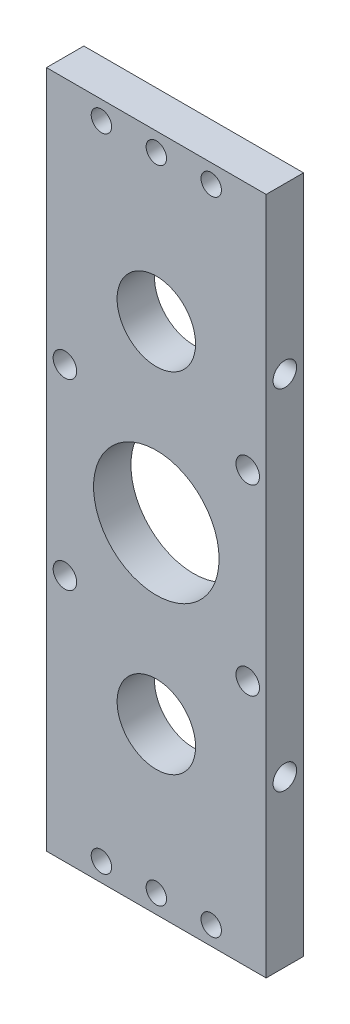
SolidWorks part; units mm, degrees
ref_plane "Plano frontal" through (0, 0, 0) normal (0, 0, 1) x (1, 0, 0)
ref_plane "Plano superior" through (0, 0, 0) normal (0, 1, 0) x (1, 0, 0)
ref_plane "Plano direito" through (0, 0, 0) normal (1, 0, 0) x (0, 0, -1)
sketch "Esboço1" plane through (0, 0, 0) normal (0, 0, 1) x (1, 0, 0)
  line L0 (28, 86.5) -> (-28, -86.5) construction
  line L1 (-28, 86.5) -> (28, 86.5)
  line L2 (-28, 86.5) -> (-28, -86.5)
  line L3 (-28, -86.5) -> (28, -86.5)
  line L4 (28, 86.5) -> (28, -86.5)
  dimension "D1" = 173
  dimension "D2" = 56
extrude "Ressalto-extrusão1" add sketch "Esboço1" along normal blind 9.525
sketch "Esboço2" plane through (0, 0, 9.525) normal (0, 0, 1) x (1, 0, 0)
  line L0 (0, 86.5) -> (0, -86.5) construction
  line L1 (28, 86.5) -> (-28, 86.5) construction
  line L2 (-28, -86.5) -> (28, -86.5) construction
  line L3 (0, 0) -> (-16, 0) construction
  line L4 (-28, 81.74) -> (28, 81.74) construction
  line L5 (-28, 86.5) -> (-28, -86.5) construction
  line L6 (28, -86.5) -> (28, 86.5) construction
  circle A0 centre (0, 0) radius 16
  circle A1 centre (0, 44.47) radius 10
  circle A2 centre (0, -44.47) radius 10
  circle A7 centre (0, 81.74) radius 2.6
  circle A8 centre (14, 81.74) radius 2.6
  circle A9 centre (-14, 81.74) radius 2.6
  circle A10 centre (14, -81.74) radius 2.6
  circle A11 centre (0, -81.74) radius 2.6
  circle A12 centre (-14, -81.74) radius 2.6
  dimension "D1" = 32
  dimension "D3" = 20
  dimension "D9" = 5.2
  dimension "D10" = 5.2
  dimension "D2" = 44.47
  dimension "D7" = 4.76
  dimension "D8" = 14
extrude "Corte-extrusão1" cut sketch "Esboço2" against normal up to surface (9.525 mm away) up to face at (0, 0, 0)
sketch "Croquis1" plane through (28, 0, 0) normal (1, 0, 0) x (0, 0, -1)
  line L0 (-4.7625, -86.5) -> (-4.7625, 86.5) construction
  line L1 (-9.525, -86.5) -> (0, -86.5) construction
  line L2 (-9.525, 86.5) -> (0, 86.5) construction
  circle A0 centre (-4.7625, -44.47) radius 2
  circle A1 centre (-4.7625, 44.47) radius 2
  dimension "D1" = 4
  dimension "D2" = 4
  dimension "D3" = 42.03
  dimension "D4" = 42.03
extrude "Cortar-Extruir2" cut sketch "Croquis1" against normal up to next
sketch "Croquis2" plane through (28, 0, 0) normal (1, 0, 0) x (0, 0, -1)
  circle A0 centre (-4.7625, -44.47) radius 3
  circle A1 centre (-4.7625, 44.47) radius 3
  dimension "D1" = 6
  dimension "D2" = 6
extrude "Cortar-Extruir3" cut sketch "Croquis2" against normal blind 7
sketch "Esboço3" plane through (0, 0, 9.525) normal (0, 0, 1) x (1, 0, 0)
  circle A0 centre (-23.3, 23.3) radius 3
  circle A1 centre (23.3, 23.3) radius 3
  circle A2 centre (23.3, -23.3) radius 3
  circle A3 centre (-23.3, -23.3) radius 3
extrude "Corte-extrusão2" cut sketch "Esboço3" against normal through all
